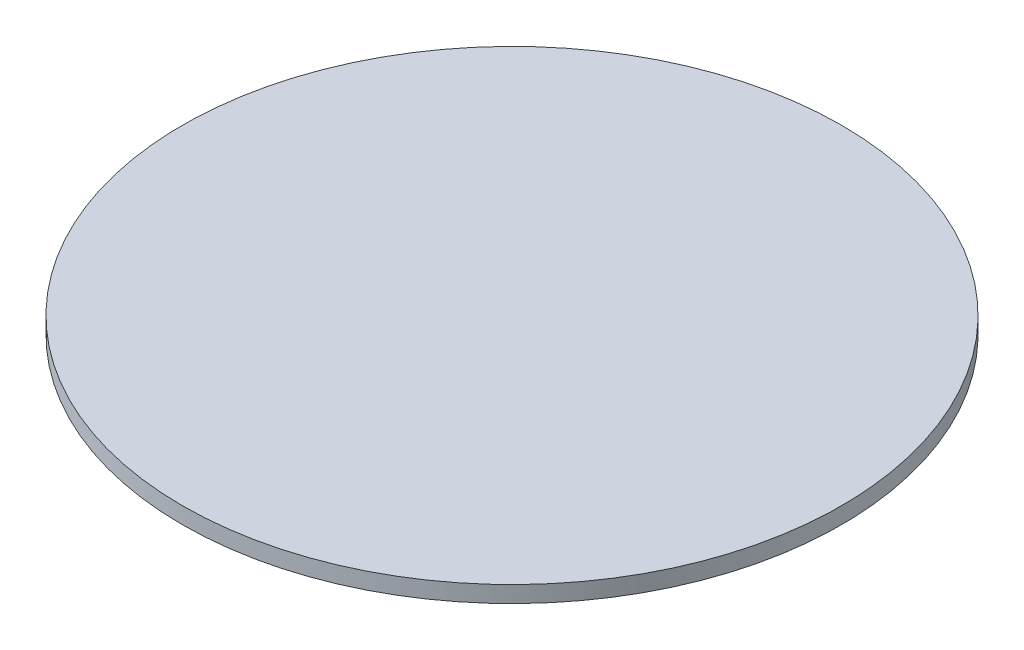
SolidWorks part; units mm, degrees
ref_plane "前视基准面" through (0, 0, 0) normal (0, 0, 1) x (1, 0, 0)
ref_plane "上视基准面" through (0, 0, 0) normal (0, 1, 0) x (1, 0, 0)
ref_plane "右视基准面" through (0, 0, 0) normal (1, 0, 0) x (0, 0, -1)
sketch "草图1" plane through (0, 0, 0) normal (0, 1, 0) x (1, 0, 0)
  circle A0 centre (0, 0) radius 30
  dimension "D1" = 60
extrude "凸台-拉伸1" add sketch "草图1" along normal blind 1.5
